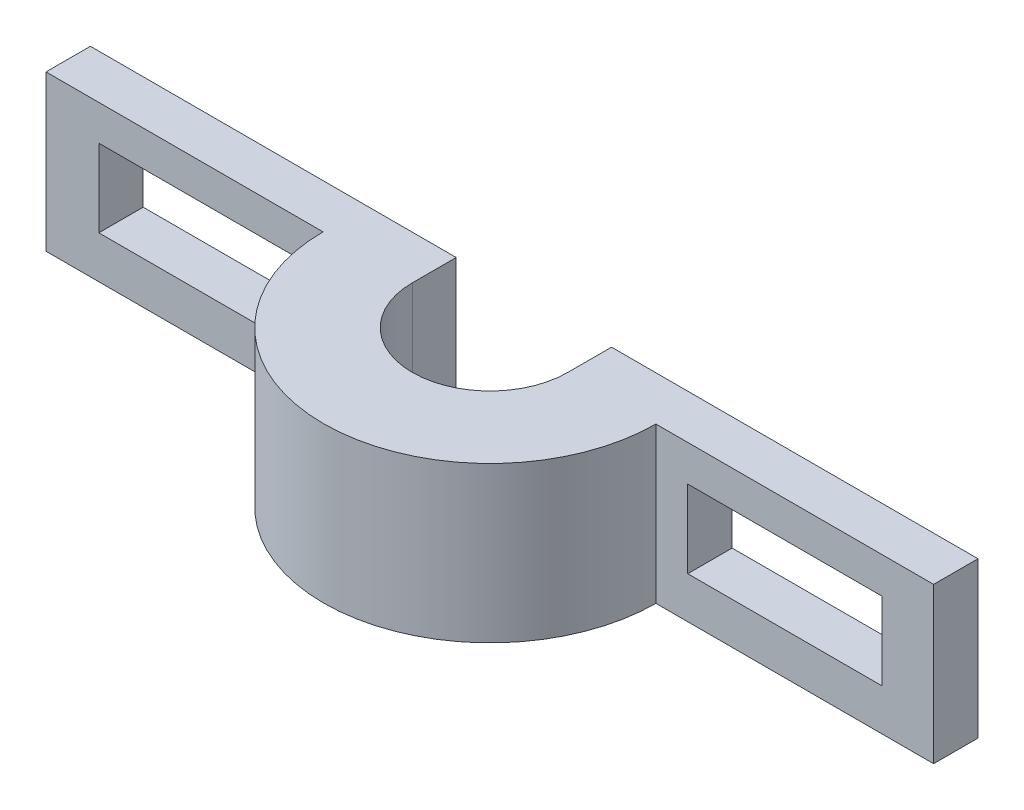
SolidWorks part; units mm, degrees
ref_plane "前视基准面" through (0, 0, 0) normal (0, 0, 1) x (1, 0, 0)
ref_plane "上视基准面" through (0, 0, 0) normal (0, 1, 0) x (1, 0, 0)
ref_plane "右视基准面" through (0, 0, 0) normal (1, 0, 0) x (0, 0, -1)
other "Configuration Table"
sketch "草图1" plane through (0, 0, 0) normal (0, 1, 0) x (1, 0, 0)
  circle A0 centre (0, 0) radius 7.5
  dimension "D1" = 15
extrude "凸台-拉伸4" add sketch "草图1" along normal blind 7
sketch "草图4" plane through (0, 0, 0) normal (0, -1, 0) x (1, 0, 0)
  line L1 (-19.9853, 0.0248) -> (20.0147, 0.0248)
  line L2 (-19.9853, 0.0248) -> (-19.9853, -1.9752)
  line L3 (-19.9853, -1.9752) -> (20.0147, -1.9752)
  line L4 (20.0147, 0.0248) -> (20.0147, -1.9752)
  dimension "D1" = 2
  dimension "D2" = 40
extrude "凸台-拉伸5" add sketch "草图4" against normal blind 7 contours L2 L1 L4 L3
sketch "草图5" plane through (0, 0, 0) normal (0, -1, 0) x (-1, 0, 0)
  line L1 (7.2352, 1.9752) -> (-9.1852, 1.9752)
  line L2 (7.2352, 1.9752) -> (7.2352, 9.1287)
  line L3 (7.2352, 9.1287) -> (-9.1852, 9.1287)
  line L4 (-9.1852, 1.9752) -> (-9.1852, 9.1287)
extrude "切除-拉伸1" cut sketch "草图5" against normal blind 7
sketch "草图6" plane through (0, 0, 0) normal (0, -1, 0) x (1, 0, 0)
  line L0 (-7.5, 0.0248) -> (-5.5, 0.0248)
  line L1 (7.5, 0.0248) -> (5.5, 0.0248)
  line L2 (-5.5, 0.0248) -> (5.5, -0.0248)
  arc A0 (5.5, 0.0248) -> (-5.4985, 0.1293) centre (0, 0) ccw
  circle A1 centre (0, 0) radius 5.5
  dimension "D1" = 2
  dimension "D2" = 2
extrude "切除-拉伸2" cut sketch "草图6" against normal blind 7 contours A1
sketch "草图7" plane through (0, 7, 0) normal (0, 1, 0) x (1, 0, 0)
  line L0 (5.1331, 1.9752) -> (20.0147, 1.9752) construction
  line L1 (-5.5, 0) -> (5.5, 0)
  line L2 (-5.5, 0) -> (-5.5, 1.9752)
  line L3 (-5.5, 1.9752) -> (5.5, 1.9752)
  line L4 (5.5, 0) -> (5.5, 1.9752)
  arc A0 (-5.1331, 1.9752) -> (5.1331, 1.9752) centre (0, 0) ccw construction
extrude "切除-拉伸3" cut sketch "草图7" against normal blind 7
sketch "草图9" plane through (0, 0, 0.0248) normal (0, 0, 1) x (1, 0, 0)
  line L0 (-18.605, 5.4097) -> (-8.8492, 5.4097)
  line L1 (8.9343, 5.3757) -> (18.6901, 5.3757)
  line L2 (8.9343, 5.3757) -> (8.9343, 1.8757)
  line L3 (8.9343, 1.8757) -> (18.6901, 1.8757)
  line L4 (18.6901, 5.3757) -> (18.6901, 1.8757)
  line L5 (-18.605, 5.4097) -> (-18.605, 1.9097)
  line L6 (-18.605, 1.9097) -> (-8.8492, 1.9097)
  line L7 (-8.8492, 5.4097) -> (-8.8492, 1.9097)
  dimension "D1" = 3.5
extrude "切除-拉伸4" cut sketch "草图9" against normal blind 7
sketch "草图10" plane through (0, 0, 0.0248) normal (0, 0, 1) x (1, 0, 0)
  line L0 (8.9343, 1.8757) -> (18.6901, 1.8757) construction
  line L1 (18.6901, 5.3757) -> (17.6901, 5.3757)
  line L2 (18.6901, 5.3757) -> (18.6901, 1.8757)
  line L3 (18.6901, 1.8757) -> (17.6901, 1.8757)
  line L4 (17.6901, 5.3757) -> (17.6901, 1.8757)
  dimension "D1" = 1
extrude "凸台-拉伸6" add sketch "草图10" against normal blind 2
sketch "草图11" plane through (0, 0, 0.0248) normal (0, 0, 1) x (1, 0, 0)
  line L0 (-18.605, 1.9097) -> (-8.8492, 1.9097) construction
  line L1 (-18.605, 5.4097) -> (-17.605, 5.4097)
  line L2 (-18.605, 5.4097) -> (-18.605, 1.9097)
  line L3 (-18.605, 1.9097) -> (-17.605, 1.9097)
  line L4 (-17.605, 5.4097) -> (-17.605, 1.9097)
  dimension "D1" = 1
extrude "凸台-拉伸7" add sketch "草图11" against normal blind 2
sketch "草图12" plane through (0, 0, 0) normal (0, -1, 0) x (-1, 0, 0)
  circle A0 centre (0, 0) radius 5.9442
extrude "凸台-拉伸8" add sketch "草图12" against normal blind 7
sketch "草图13" plane through (0, 0, 0) normal (0, -1, 0) x (-1, 0, 0)
  line L1 (5.6064, 1.9752) -> (-8.4326, 1.9752)
  line L2 (5.6064, 1.9752) -> (5.6064, 6.4275)
  line L3 (5.6064, 6.4275) -> (-8.4326, 6.4275)
  line L4 (-8.4326, 1.9752) -> (-8.4326, 6.4275)
extrude "切除-拉伸5" cut sketch "草图13" against normal blind 7
sketch "草图14" plane through (0, 0, 0) normal (0, -1, 0) x (1, 0, 0)
  circle A0 centre (0, 0) radius 3.5
extrude "切除-拉伸6" cut sketch "草图14" against normal blind 7
sketch "草图15" plane through (0, 0, 0) normal (0, -1, 0) x (1, 0, 0)
  line L0 (2.8894, -1.9752) -> (20.0147, -1.9752) construction
  line L1 (-3.5, 0) -> (3.5, 0)
  line L2 (-3.5, 0) -> (-3.5, -1.9752)
  line L3 (-3.5, -1.9752) -> (3.5, -1.9752)
  line L4 (3.5, 0) -> (3.5, -1.9752)
  arc A0 (2.8894, -1.9752) -> (-2.8894, -1.9752) centre (0, 0) ccw construction
extrude "切除-拉伸7" cut sketch "草图15" against normal blind 7
